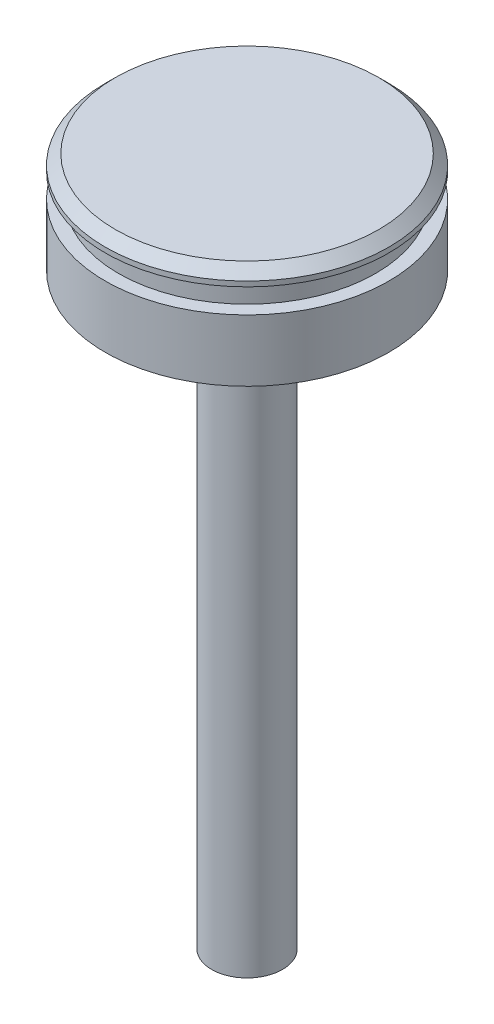
SolidWorks part; units mm, degrees
material "6061-T6 (SS)"
ref_plane "Piano frontale" through (0, 0, 0) normal (0, 0, 1) x (1, 0, 0)
ref_plane "Piano superiore" through (0, 0, 0) normal (0, 1, 0) x (1, 0, 0)
ref_plane "Piano destro" through (0, 0, 0) normal (1, 0, 0) x (0, 0, -1)
sketch "Schizzo1" plane through (0, 0, 0) normal (0, 0, 1) x (1, 0, 0)
  line L0 (0, 0) -> (0, 68)
  line L1 (0, 0) -> (-3.5, 0)
  line L2 (-3.5, 0) -> (-3.5, 58)
  line L3 (-3.5, 58) -> (-14, 58)
  line L4 (-14, 58) -> (-14, 68)
  line L5 (-14, 68) -> (0, 68)
  line L6 (0, 0) -> (0, 44.4338) construction
  line L10 (-14, 66.5) -> (-12.7, 66.5)
  line L11 (-12.7, 66.5) -> (-12.7, 64.1)
  line L12 (-12.7, 64.1) -> (-14, 64.1)
  dimension "D1" = 7
  dimension "D2" = 28
  dimension "D3" = 10
  dimension "D4" = 58
  dimension "D5" = 2.4
  dimension "D6" = 1.3
  dimension "D10" = 1.5
revolve "Rivoluzione1" add sketch "Schizzo1" angle 360 about L6
cosmetic thread "Filettatura cosmetica1"
chamfer "Smusso1" distance 1 angle 45 1 edges at (0, 68, -14)
